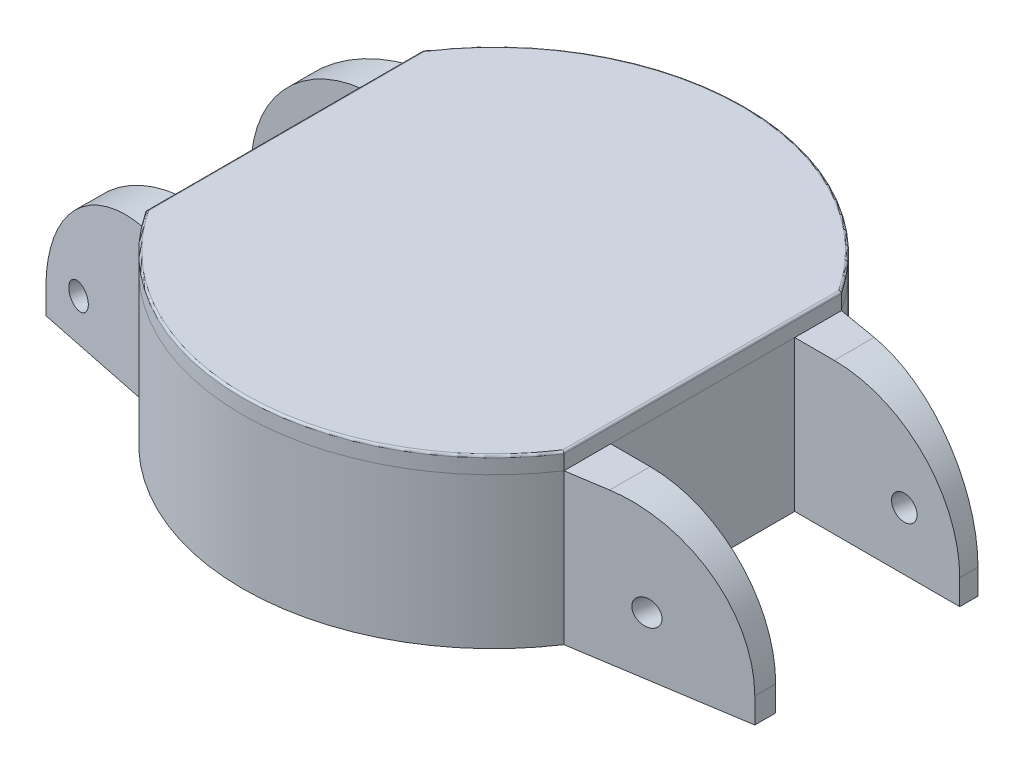
SolidWorks part; units mm, degrees
ref_plane "Front Plane" through (0, 0, 0) normal (0, 0, 1) x (1, 0, 0)
ref_plane "Top Plane" through (0, 0, 0) normal (0, 1, 0) x (1, 0, 0)
ref_plane "Right Plane" through (0, 0, 0) normal (1, 0, 0) x (0, 0, -1)
sketch "Sketch1" plane through (0, 0, 0) normal (0, 1, 0) x (1, 0, 0)
  line L2 (25, 16.5831) -> (25, -16.5831)
  line L4 (-25, 16.5831) -> (-25, -16.5831)
  line L5 (25, 30.0214) -> (-19.1974, -23.0534) construction
  line L6 (19.1974, -23.0534) -> (-19.1974, 23.0534) construction
  arc A0 (-25, -16.5831) -> (25, -16.5831) centre (0, 0) ccw
  arc A1 (25, 16.5831) -> (-25, 16.5831) centre (0, 0) ccw
  dimension "D1" = 60
extrude "Boss-Extrude2" add sketch "Sketch1" along normal blind 18
shell "Shell1" thickness 1.5
sketch "Sketch2" plane through (0, 18, 0) normal (0, 1, 0) x (1, 0, 0)
  line L2 (-25, 16.5831) -> (-25, -16.5831)
  line L3 (25, -16.5831) -> (25, 16.5831)
  line L4 (-25, 16.5831) -> (-25, -16.5831)
  line L5 (25, -16.5831) -> (25, 16.5831)
  arc A2 (25, 16.5831) -> (-25, 16.5831) centre (0, 0) ccw
  arc A3 (-25, -16.5831) -> (25, -16.5831) centre (0, 0) ccw
  arc A4 (25, 16.5831) -> (-25, 16.5831) centre (0, 0) ccw
  arc A5 (-25, -16.5831) -> (25, -16.5831) centre (0, 0) ccw
  dimension "D1" = 0
extrude "Boss-Extrude3" add sketch "Sketch2" along normal blind 2 separate body
sketch "Sketch3" plane through (0, 18, 0) normal (0, -1, 0) x (1, 0, 0)
  line L4 (23.3, -16.0624) -> (23.3, 16.0624)
  line L5 (-23.3, 16.0624) -> (-23.3, -16.0624)
  line L6 (23.3, -16.0624) -> (23.3, 16.0624)
  line L7 (-23.3, 16.0624) -> (-23.3, -16.0624)
  arc A4 (-23.3, -16.0624) -> (23.3, -16.0624) centre (0, 0) ccw
  arc A5 (23.3, 16.0624) -> (-23.3, 16.0624) centre (0, 0) ccw
  arc A6 (-23.3, -16.0624) -> (23.3, -16.0624) centre (0, 0) ccw
  arc A7 (23.3, 16.0624) -> (-23.3, 16.0624) centre (0, 0) ccw
  dimension "D1" = 1.7
extrude "Boss-Extrude4" add sketch "Sketch3" along normal blind 1
sketch "Sketch5" plane through (0, 20, 0) normal (0, 1, 0) x (1, 0, 0)
  line L0 (-40, 11) -> (-25, 11)
  line L1 (-40, 11) -> (-40, 13.5046)
  line L2 (-25, 11) -> (-25, 16.5831)
  line L3 (-40, -11) -> (-25, -11)
  line L4 (-40, -13.5) -> (-40, -11)
  line L5 (-25, 16.5831) -> (-25, -16.5831) construction
  line L6 (-25, 16.5831) -> (-40, 13.5046)
  line L7 (-25, -16.5831) -> (-40, -13.5)
  line L8 (40, -13.5) -> (40, -11)
  line L9 (25, -16.5831) -> (25, 16.5831) construction
  line L10 (24.7559, 16.6502) -> (40, 13.5)
  line L11 (25, -16.5831) -> (40, -13.5)
  line L12 (25, -11) -> (40, -11)
  line L13 (40, 11) -> (25, 11)
  line L14 (-40, 11) -> (-25, 11)
  line L15 (40, 11) -> (40, 13.5)
  line L16 (-24.9654, -16.8443) -> (-25, -11)
  line L17 (25.0643, -16.5589) -> (25, -11)
  line L18 (24.7855, 10.6821) -> (24.7559, 16.6502)
  line L19 (-40, -11) -> (-25, -11)
  line L20 (25, -11) -> (40, -11)
  line L21 (24.7839, 11) -> (40, 11)
  point P7 (0, 0)
  point P12 (0, 0)
  point P14 (20, 11)
  point P17 (-27.337, -11)
  dimension "D1" = 22
  dimension "D2" = 22
  dimension "D3" = 15
  dimension "D6" = 15
sketch "Sketch7" plane through (0, 18, 0) normal (0, 1, 0) x (1, 0, 0)
  line L1 (-29.3134, -37.0772) -> (29.3134, -37.0772)
  line L2 (-29.3134, -37.0772) -> (-29.3134, 37.0772)
  line L3 (-29.3134, 37.0772) -> (29.3134, 37.0772)
  line L4 (29.3134, -37.0772) -> (29.3134, 37.0772)
  line L5 (-29.3134, -37.0772) -> (29.3134, 37.0772) construction
  line L6 (-29.3134, 37.0772) -> (29.3134, -37.0772) construction
  line L10 (-24.9654, -16.8443) -> (-25, -11)
  line L11 (-25, -11) -> (-40, -11)
  line L12 (-40, -11) -> (-40, -13.5)
  line L13 (-40, -13.5) -> (-25, -16.5831)
  line L14 (-25, 16.5831) -> (-40, 13.1817)
  line L15 (-40, 13.1817) -> (-40, 11)
  line L16 (-40, 11) -> (-25, 11)
  line L17 (-25, 16.5831) -> (-25, -16.5831) construction
  line L18 (-25, 11) -> (-25, 16.5831)
  line L19 (25, 16.5831) -> (44.7251, 13.1817)
  line L20 (44.7251, 13.1817) -> (44.7251, 11)
  line L21 (44.7251, 11) -> (25, 11)
  line L22 (25, -16.5831) -> (25, 16.5831) construction
  line L23 (25, 11) -> (25, 16.5831)
  line L24 (25, -16.5831) -> (44.7251, -13.5)
  line L25 (44.7251, -13.5) -> (44.7251, -11)
  line L26 (44.7251, -11) -> (25, -11)
  line L27 (25, -11) -> (25, -16.5831)
  point P0 (0, 0)
  line M6 (-25, 16.5831) -> (-25, -16.5831)
  line M8 (25, -16.5831) -> (25, 16.5831)
  dimension "D1" = 22
  dimension "D2" = 22
  dimension "D3" = 5.8444
  dimension "D4" = 5.5831
extrude "Boss-Extrude7" add sketch "Sketch7" against normal blind 18 contours L25 L26 L4 L24 | L4 L26 L24 M8 | L21 L4 L19 M8 | L21 L20 L19 L4 | L15 L16 L2 L14 | L2 L13 L11 M6 | L12 L13 L2 L11
fillet "Fillet7" radius 0.25 4 edges at (25, 20, 0) (0, 20, 30) (-25, 20, 0) (0, 20, -30)
sketch "Sketch9" plane through (0, 0, 0) normal (0, 0, 1) x (1, 0, 0)
  line L0 (2.9498, 7.2176) -> (-6.1502, 7.2176) construction
  line L1 (2.9498, 5.3176) -> (-6.1502, 5.3176)
  line L2 (2.9498, 9.1176) -> (-6.1502, 9.1176)
  arc A0 (2.9498, 5.3176) -> (2.9498, 9.1176) centre (2.9498, 7.2176) ccw
  arc A1 (-6.1502, 9.1176) -> (-6.1502, 5.3176) centre (-6.1502, 7.2176) ccw
  point P2 (-1.6002, 7.2176)
  dimension "D1" = 9.1
  dimension "D2" = 3.8
extrude "Cut-Extrude4" cut sketch "Sketch9" against normal through all
sketch "Sketch10" plane through (3.499, 0, -20.2908) normal (0.1699, 0, -0.9855) x (-0.9855, 0, -0.1699)
  circle A0 centre (-35.6767, 6.9415) radius 1.5
  dimension "D1" = 3
extrude "Cut-Extrude5" cut sketch "Sketch10" against normal through all
sketch "Sketch11" plane through (-4.7992, 0, -21.1639) normal (-0.2211, 0, -0.9752) x (-0.9752, 0, 0.2211)
  line L0 (36.0945, 0) -> (36.0945, 18) construction
  line L1 (20.7137, 0) -> (36.0945, 0) construction
  circle A0 centre (31.0945, 5) radius 1.5
  dimension "D1" = 3
  dimension "D2" = 5
  dimension "D3" = 5
extrude "Cut-Extrude7" cut sketch "Sketch11" against normal blind 10
sketch "Sketch12" plane through (-4.2837, 0, 20.8412) normal (-0.2013, 0, 0.9795) x (0.9795, 0, 0.2013)
  line L0 (-36.4629, 0) -> (-21.1493, 0) construction
  line L1 (-36.4629, 0) -> (-36.4629, 18) construction
  circle A0 centre (-31.4629, 5) radius 1.5
  dimension "D1" = 3
  dimension "D2" = 5
  dimension "D3" = 5
extrude "Cut-Extrude8" cut sketch "Sketch12" against normal blind 10
sketch "Sketch13" plane through (0, 0, 0) normal (0, -1, 0) x (1, 0, 0)
  line L0 (25, 11) -> (25, -11) construction
  line L5 (22, -10.1512) -> (16, -10.1512)
  line L6 (22, -10.1512) -> (22, 10.8488)
  line L7 (22, 10.8488) -> (16, 10.8488)
  line L8 (16, -10.1512) -> (16, 10.8488)
  point P4 (19, -10.1512)
  dimension "D1" = 3
  dimension "D2" = 21
  dimension "D3" = 3
extrude "Cut-Extrude10" cut sketch "Sketch13" against normal blind 10
fillet "Fillet10" radius 15 4 edges at (44.7251, 18, -12.0908) (44.7251, 18, 12.25) (-40, 18, -12.0908) (-40, 18, 12.25)
